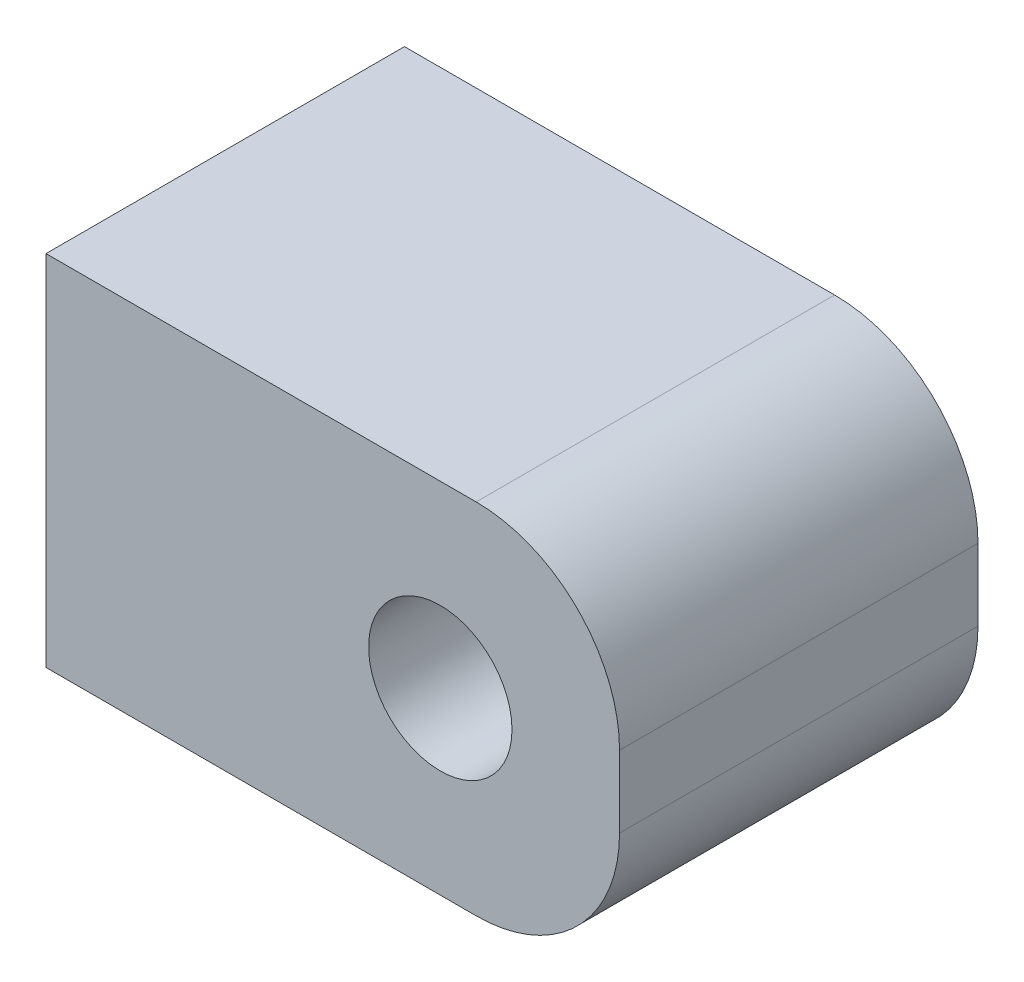
SolidWorks part; units mm, degrees
ref_plane "Front Plane" through (0, 0, 0) normal (0, 0, 1) x (1, 0, 0)
ref_plane "Top Plane" through (0, 0, 0) normal (0, 1, 0) x (1, 0, 0)
ref_plane "Right Plane" through (0, 0, 0) normal (1, 0, 0) x (0, 0, -1)
sketch "Sketch1" plane through (0, 0, 0) normal (0, 0, 1) x (1, 0, 0)
  line L1 (0, 0) -> (8, 0)
  line L2 (0, 0) -> (0, 5)
  line L3 (0, 5) -> (8, 5)
  line L4 (8, 0) -> (8, 5)
  dimension "D1" = 5
  dimension "D2" = 8
extrude "Boss-Extrude1" add sketch "Sketch1" along normal blind 5
sketch "Sketch2" plane through (0, 0, 0) normal (-1, 0, 0) x (0, 0, 1)
  line L0 (5, 0) -> (0, 0) construction
  line L1 (0, 5) -> (0, 0) construction
  circle A0 centre (2.5, 2.5) radius 1
  dimension "D1" = 2
  dimension "D2" = 2.5
  dimension "D3" = 2.5
extrude "Cut-Extrude1" cut sketch "Sketch2" against normal blind 4
sketch "Sketch3" plane through (0, 0, 5) normal (0, 0, 1) x (1, 0, 0)
  line L0 (8, 0) -> (8, 5) construction
  line L1 (8, 5) -> (0, 5) construction
  circle A0 centre (5.5, 2.5) radius 1
  dimension "D1" = 2
  dimension "D2" = 2.5
  dimension "D3" = 2.5
extrude "Cut-Extrude4" cut sketch "Sketch3" against normal blind 5
fillet "Fillet1" radius 2 2 edges at (8, 0, 2.5) (8, 5, 2.5)
